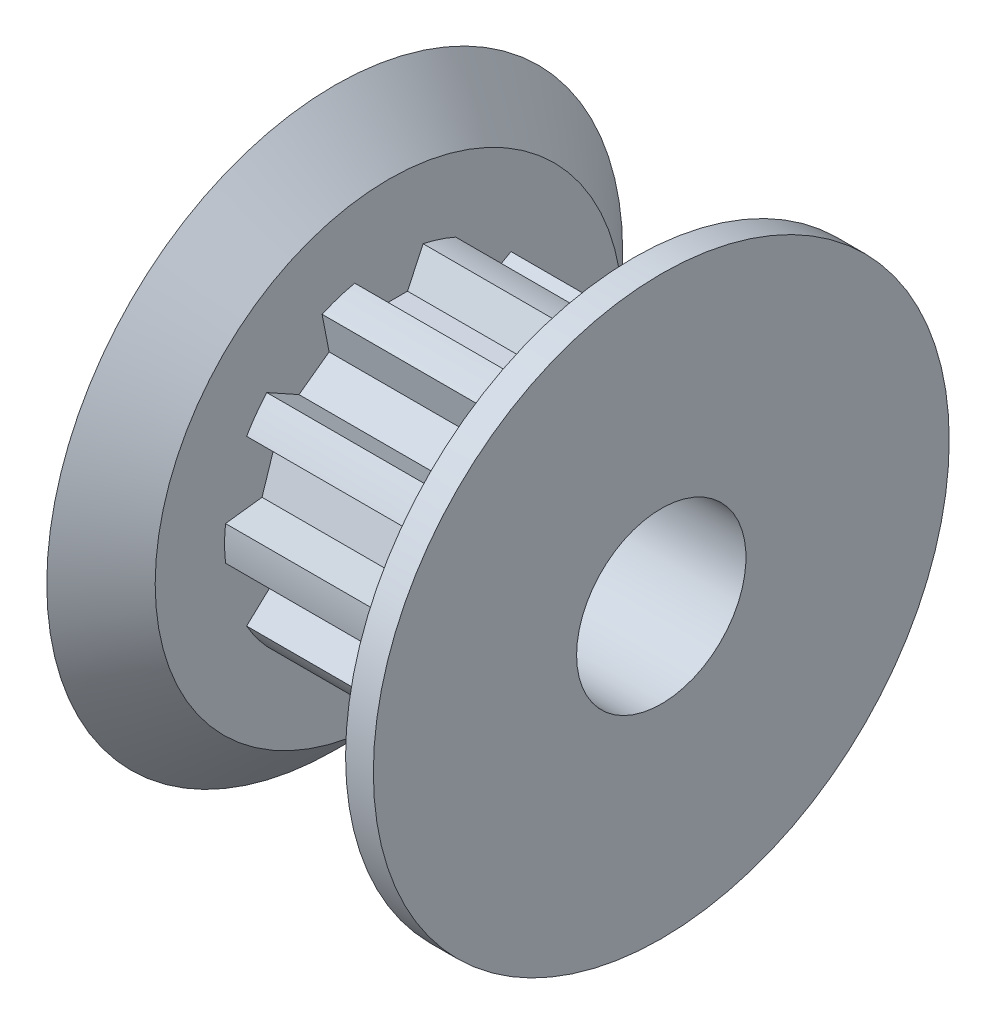
SolidWorks part; units mm, degrees
ref_plane "Front Plane" through (0, 0, 0) normal (0, 0, 1) x (1, 0, 0)
ref_plane "Top Plane" through (0, 0, 0) normal (0, 1, 0) x (1, 0, 0)
ref_plane "Right Plane" through (0, 0, 0) normal (1, 0, 0) x (0, 0, -1)
sketch "Sketch2" plane through (0, 0, 0) normal (1, 0, 0) x (0, 0, -1)
  line L3 (0, 0) -> (0, 2.413) construction
  line L6 (0, -2.921) -> (0, -3.2385) construction
  line L7 (-0.5715, 2.8645) -> (-0.3491, 2.3876)
  line L8 (0.5715, 2.8645) -> (0.3491, 2.3876)
  line L9 (-0.5715, 2.8645) -> (-0.6405, 3.0124)
  line L10 (0.5715, 2.8645) -> (0.6405, 3.0124)
  line L12 (-0.3491, 2.3876) -> (0.3491, 2.3876)
  line L14 (0, 2.921) -> (0, 3.2385) construction
  line L15 (0, 0) -> (0, -1.143) construction
  circle A0 centre (0, 0) radius 3.2385 construction
  circle A1 centre (0, 0) radius 2.413 construction
  circle A2 centre (0, 0) radius 2.921 construction
  arc A7 (0.6405, 3.0124) -> (-0.6405, 3.0124) centre (0, 0) ccw
  point P5 (0, 3.0798)
  dimension "D3" = 0.3175
  dimension "D1" = 50
sketch "Sketch1" plane through (0, 0, 0) normal (0, 0, 1) x (1, 0, 0)
  line L0 (-5.5626, 0) -> (5.5626, 0) construction
  line L1 (-0.5588, 5.3975) -> (-0.5588, 1.5875)
  line L2 (-0.5588, 1.5875) -> (5.5626, 1.5875)
  line L4 (-0.5588, 5.3975) -> (0.4572, 4.3815)
  line L5 (0.4572, 4.3815) -> (0.4572, 3.2385)
  line L6 (0.4572, 3.2385) -> (4.5212, 3.2385)
  line L7 (4.5212, 3.2385) -> (4.5212, 3.81)
  line L8 (4.5212, 3.2385) -> (5.5626, 3.2385) construction
  line L9 (5.0419, 5.3975) -> (5.5626, 5.3975)
  line L10 (5.5626, 5.3975) -> (5.5626, 1.5875)
  line L11 (5.0419, 3.2385) -> (5.0419, 5.3975) construction
  line L12 (-3.0607, 5.3975) -> (-3.0607, 1.5875) construction
  arc A0 (4.5212, 3.81) -> (5.0419, 5.3975) centre (7.2015, 3.81) cw
  dimension "Overall Width" = 11.1252
  dimension "Inside Width" = 4.064
  dimension "Outside Width" = 5.1054
  dimension "OD" = 10.795
  dimension "D1" = 45
  dimension "D2" = 6.477
  dimension "D3" = 1.143
  dimension "D4" = 0.5715
revolve "Revolve1" add sketch "Sketch1" angle 360 mid plane about L0
sketch "Sketch4" plane through (0.4572, 0, 0) normal (1, 0, 0) x (0, 0, -1)
  circle A0 centre (0, 0) radius 3.0798
  circle A1 centre (0, 0) radius 3.2385 construction
  circle A2 centre (0, 0) radius 3.2385
extrude "Cut-Extrude2" cut sketch "Sketch4" along normal up to surface (4.064 mm away) up to face at (4.5212, 0, 3.2385)
sketch "Sketch3" plane through (0.4572, 0, 0) normal (1, 0, 0) x (0, 0, -1)
  line L2 (-0.5715, 2.8645) -> (-0.3491, 2.3876) construction
  line L3 (-0.3491, 2.3876) -> (0.3491, 2.3876) construction
  line L4 (0.5715, 2.8645) -> (0.3491, 2.3876) construction
  line L5 (-0.6405, 3.0124) -> (-0.3491, 2.3876)
  line L6 (-0.3491, 2.3876) -> (0.3491, 2.3876)
  line L7 (0.6405, 3.0124) -> (0.3491, 2.3876)
  arc A1 (0.6405, 3.0124) -> (-0.6405, 3.0124) centre (0, 0) ccw construction
  arc A2 (0.6405, 3.0124) -> (-0.6405, 3.0124) centre (0, 0) ccw
extrude "Cut-Extrude1" cut sketch "Sketch3" along normal up to surface (4.064 mm away)
pattern_circular "CirPattern1" count 10 over 360 about axis through (0, 0, 0) along (1, 0, 0) of "Cut-Extrude1"
sketch "Sketch5" plane through (0, 0, 0) normal (0, 0, 1) x (1, 0, 0)
  line L1 (4.5212, 3.81) -> (4.5212, -3.81) construction
  point P0 (4.5212, 0)
equation "\"D3@Sketch2\" = (\"hs@Sketch2\"-\"ht@Sketch2\")/2"
equation "\"D2@Sketch1\" = \"PD@Sketch2\""
equation "\"D3@Sketch1\" = \"hs@Sketch2\""
equation "\"D4@Sketch1\" = \"D3@Sketch1\"/2"
